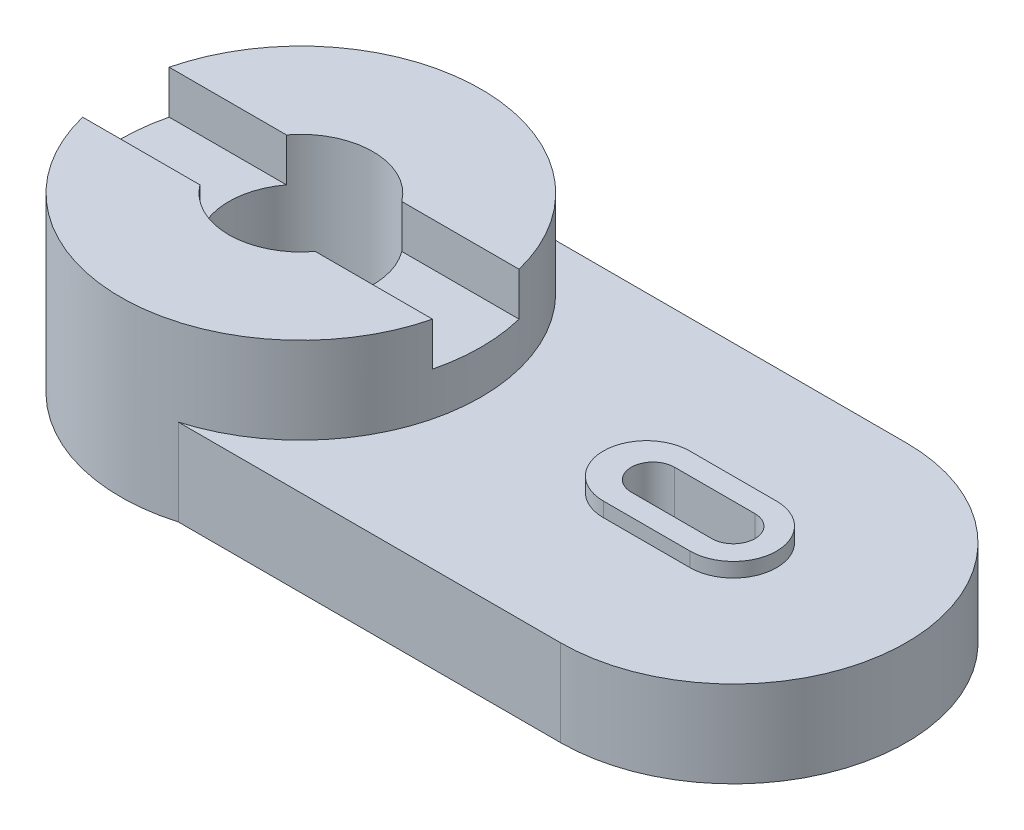
SolidWorks part; units mm, degrees
ref_plane "Front Plane" through (0, 0, 0) normal (0, 0, 1) x (1, 0, 0)
ref_plane "Top Plane" through (0, 0, 0) normal (0, 1, 0) x (1, 0, 0)
ref_plane "Right Plane" through (0, 0, 0) normal (1, 0, 0) x (0, 0, -1)
sketch "Sketch2" plane through (0, 0, 0) normal (0, 1, 0) x (1, 0, 0)
  line L1 (-76.2, -60.96) -> (76.2, -60.96)
  line L2 (-76.2, -60.96) -> (-76.2, 60.96)
  line L3 (-76.2, 60.96) -> (76.2, 60.96)
  line L4 (76.2, -60.96) -> (76.2, 60.96)
  point P0 (0, 0)
  dimension "D1" = 121.92
  dimension "D2" = 152.4
extrude "Boss-Extrude1" add sketch "Sketch2" along normal blind 30.48
sketch "Sketch3" plane through (0, 30.48, 0) normal (0, 1, 0) x (1, 0, 0)
  line L0 (-76.2, 60.96) -> (-76.2, -60.96) construction
  circle A0 centre (-76.2, 0) radius 63.5
  dimension "D1" = 127
extrude "Boss-Extrude2" add sketch "Sketch3" along normal mid plane 60.96
sketch "Sketch4" plane through (0, 60.96, 0) normal (0, 1, 0) x (1, 0, 0)
  circle A0 centre (-76.2, 0) radius 25.4
  dimension "D1" = 50.8
extrude "Cut-Extrude1" cut sketch "Sketch4" against normal blind 60.96
sketch "Sketch5" plane through (0, 30.48, 0) normal (0, 1, 0) x (1, 0, 0)
  line L0 (76.2, -60.96) -> (76.2, 60.96) construction
  line L1 (-58.42, -60.96) -> (76.2, -60.96) construction
  line L2 (76.2, 60.96) -> (76.2, -60.96)
  arc A0 (76.2, 60.96) -> (76.2, -60.96) centre (76.2, 0) cw
extrude "Boss-Extrude3" add sketch "Sketch5" against normal blind 30.48
sketch "Sketch6" plane through (0, 30.48, 0) normal (0, 1, 0) x (1, 0, 0)
  line L0 (76.2, 0) -> (45.5973, 0) construction
  line L1 (76.2, -15.24) -> (45.5973, -15.24)
  line L2 (76.2, 15.24) -> (45.5973, 15.24)
  arc A0 (76.2, -15.24) -> (76.2, 15.24) centre (76.2, 0) ccw
  arc A1 (45.5973, 15.24) -> (45.5973, -15.24) centre (45.5973, 0) ccw
  point P4 (60.8987, 0)
  dimension "D1" = 30.48
  dimension "D2" = 30.6027
extrude "Boss-Extrude5" add sketch "Sketch6" along normal blind 5.08
sketch "Sketch12" plane through (0, 35.56, 0) normal (0, 1, 0) x (1, 0, 0)
  line L0 (76.2, 0) -> (47.846, 0) construction
  line L1 (76.2, -7.62) -> (47.846, -7.62)
  line L2 (76.2, 7.62) -> (47.846, 7.62)
  arc A0 (76.2, -7.62) -> (76.2, 7.62) centre (76.2, 0) ccw
  arc A1 (47.846, 7.62) -> (47.846, -7.62) centre (47.846, 0) ccw
  point P4 (62.023, 0)
  dimension "D1" = 15.24
  dimension "D2" = 28.354
extrude "Cut-Extrude4" cut sketch "Sketch12" against normal blind 35.56
sketch "Sketch14" plane through (0, 60.96, 0) normal (0, 1, 0) x (1, 0, 0)
  line L1 (-137.8441, -15.24) -> (-14.5559, -15.24)
  line L3 (-137.8441, 15.24) -> (-14.5559, 15.24)
  line L5 (-137.8441, -15.24) -> (-14.5559, 15.24) construction
  line L6 (-137.8441, 15.24) -> (-14.5559, -15.24) construction
  circle A0 centre (-76.2, 0) radius 63.5 construction
  arc A1 (-14.5559, -15.24) -> (-14.5559, 15.24) centre (-76.2, 0) ccw
  arc A2 (-137.8441, -15.24) -> (-137.8441, 15.24) centre (-76.2, 0) cw
  point P0 (-76.2, 0)
  dimension "D1" = 30.48
extrude "Cut-Extrude5" cut sketch "Sketch14" against normal blind 15.24
equation "\"4..82.40in\"=2.4"
